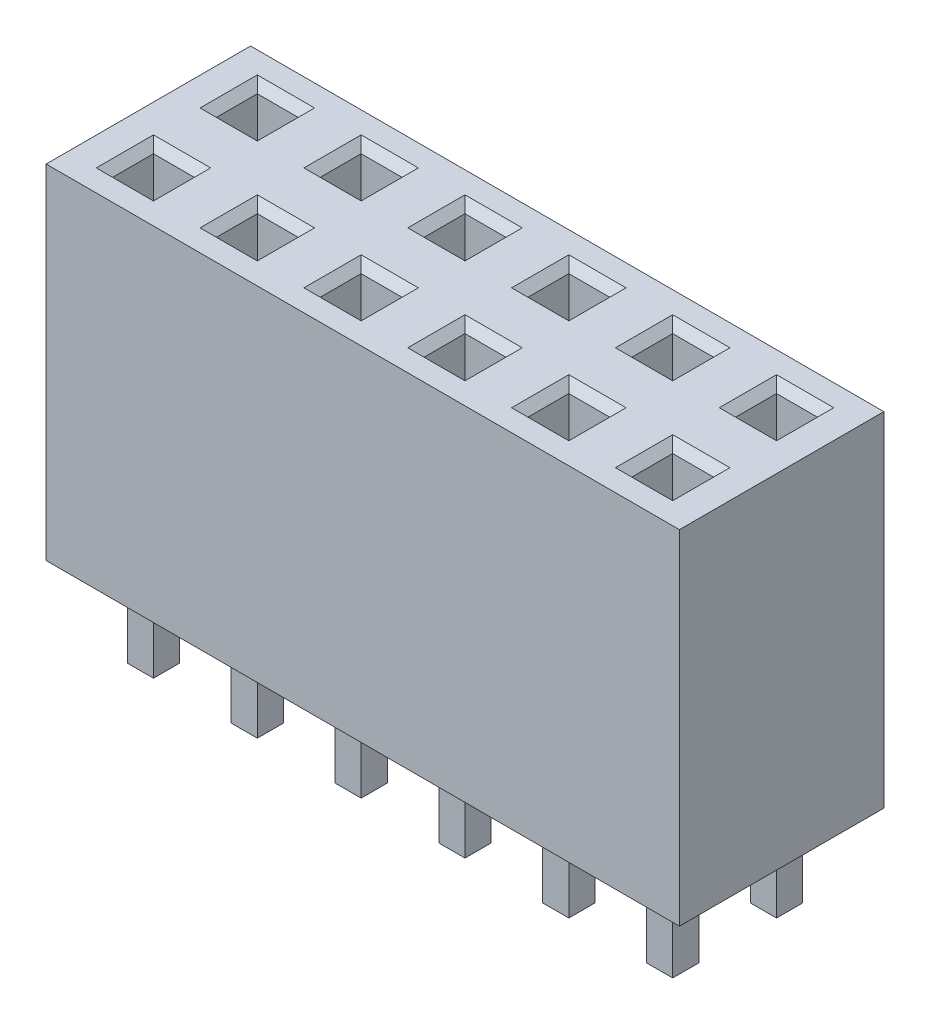
SolidWorks part; units mm, degrees
material "C (Графит)"
ref_plane "Спереди" through (0, 0, 0) normal (0, 0, 1) x (1, 0, 0)
ref_plane "Сверху" through (0, 0, 0) normal (0, 1, 0) x (1, 0, 0)
ref_plane "Справа" through (0, 0, 0) normal (1, 0, 0) x (0, 0, -1)
sketch "Эскиз1" plane through (0, 0, 0) normal (0, 1, 0) x (1, 0, 0)
  line L1 (-1.395, -2.5) -> (1.395, -2.5)
  line L2 (-1.395, -2.5) -> (-1.395, 2.5)
  line L3 (-1.395, 2.5) -> (1.395, 2.5)
  line L4 (1.395, -2.5) -> (1.395, 2.5)
  line L5 (-1.395, -2.5) -> (1.395, 2.5) construction
  line L6 (-1.395, 2.5) -> (1.395, -2.5) construction
  point P0 (0, 0)
  dimension "D1" = 5
  dimension "D2" = 2.79
extrude "Бобышка-Вытянуть1" add sketch "Эскиз1" along normal blind 8.4
sketch "Эскиз2" plane through (0, 8.4, 0) normal (0, 1, 0) x (1, 0, 0)
  line L0 (-1.395, 2.5) -> (-1.395, -2.5) construction
  line L1 (-0.5, 1.77) -> (0.5, 1.77)
  line L2 (-0.5, 1.77) -> (-0.5, 0.77)
  line L3 (-0.5, 0.77) -> (0.5, 0.77)
  line L4 (0.5, 1.77) -> (0.5, 0.77)
  line L5 (-0.5, 1.77) -> (0.5, 0.77) construction
  line L6 (-0.5, 0.77) -> (0.5, 1.77) construction
  line L7 (-1.395, 0) -> (-29.5201, 0) construction
  line L8 (0.5, -1.77) -> (0.5, -0.77)
  line L9 (-0.5, -0.77) -> (0.5, -0.77)
  line L10 (-0.5, -1.77) -> (-0.5, -0.77)
  line L11 (-0.5, -1.77) -> (0.5, -1.77)
  point P0 (0, 1.27)
  dimension "D1" = 1
  dimension "D2" = 1
  dimension "D3" = 1.395
  dimension "D4" = 1.27
extrude "Вырез-Вытянуть1" cut sketch "Эскиз2" against normal blind 8
chamfer "Фаска1" distance 0.2 angle 45 8 edges at (0.5, 8.4, -1.27) (0, 8.4, -0.77) (-0.5, 8.4, -1.27) (0, 8.4, -1.77) (0, 8.4, 1.77) (-0.5, 8.4, 1.27) (0, 8.4, 0.77) (0.5, 8.4, 1.27)
sketch "Эскиз3" plane through (0, 0, 0) normal (0, -1, 0) x (-1, 0, 0)
  line L0 (1.395, 2.5) -> (1.395, -2.5) construction
  line L1 (0.32, 0.95) -> (-0.32, 0.95)
  line L2 (0.32, 0.95) -> (0.32, 1.59)
  line L3 (0.32, 1.59) -> (-0.32, 1.59)
  line L4 (-0.32, 0.95) -> (-0.32, 1.59)
  line L5 (0.32, 0.95) -> (-0.32, 1.59) construction
  line L6 (0.32, 1.59) -> (-0.32, 0.95) construction
  line L7 (1.395, 0) -> (32.9327, 0) construction
  line L8 (0.32, -0.95) -> (-0.32, -0.95)
  line L9 (-0.32, -0.95) -> (-0.32, -1.59)
  line L10 (0.32, -1.59) -> (-0.32, -1.59)
  line L11 (0.32, -0.95) -> (0.32, -1.59)
  point P0 (0, 1.27)
  dimension "D1" = 0.64
  dimension "D2" = 0.64
  dimension "D3" = 1.395
  dimension "D4" = 2.54
extrude "Бобышка-Вытянуть2" add sketch "Эскиз3" along normal blind 2.29
chamfer "Фаска2" distance 0.2 angle 45 8 edges at (0, -2.29, -1.59) (-0.32, -2.29, -1.27) (0, -2.29, -0.95) (0.32, -2.29, -1.27) (0, -2.29, 1.59) (0.32, -2.29, 1.27) (0, -2.29, 0.95) (-0.32, -2.29, 1.27)
pattern_linear "Линейный массив1" count 6 spacing 2.54 along (1, 0, 0) of "Бобышка-Вытянуть1", "Вырез-Вытянуть1", "Фаска1", "Бобышка-Вытянуть2", "Фаска2"
